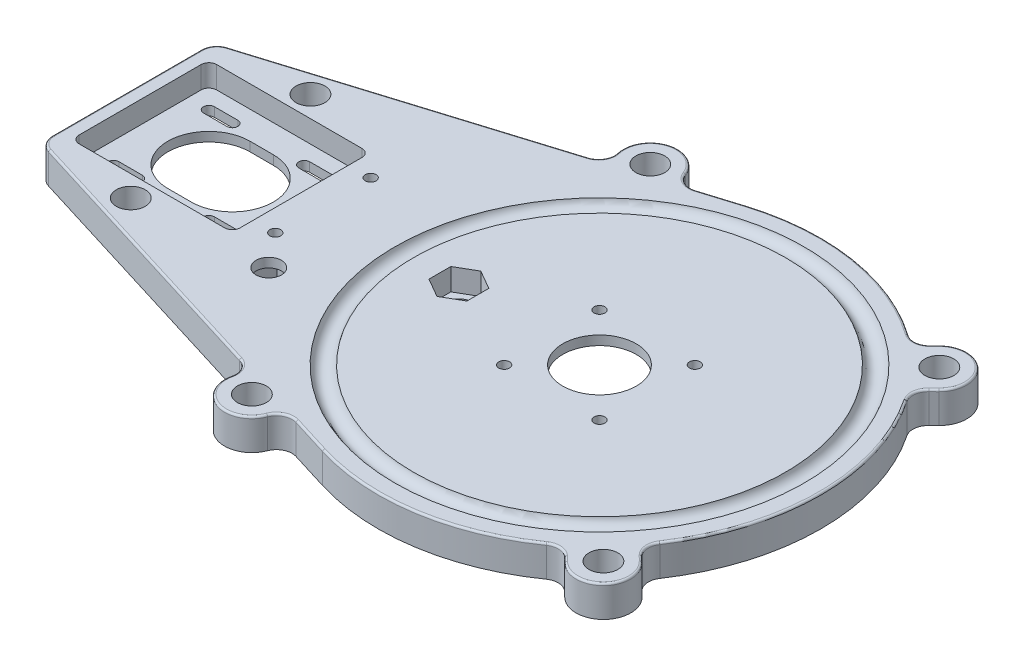
SolidWorks part; units mm, degrees
ref_plane "Front Plane" through (0, 0, 0) normal (0, 0, 1) x (1, 0, 0)
ref_plane "Top Plane" through (0, 0, 0) normal (0, 1, 0) x (1, 0, 0)
ref_plane "Right Plane" through (0, 0, 0) normal (1, 0, 0) x (0, 0, -1)
sketch "Sketch1" plane through (0, 0, 0) normal (0, 1, 0) x (1, 0, 0)
  line L0 (-153.67, 27.94) -> (-153.67, 0)
  line L5 (72.009, 0) -> (0, 0) construction
  line L6 (-153.67, 0) -> (-153.67, -27.94)
  line L7 (-21.2326, 68.8075) -> (-38.553, 63.4628)
  line L8 (-21.2326, -68.8075) -> (-38.553, -63.4628)
  line L9 (0, 0) -> (-153.67, 0) construction
  line L10 (0, 0) -> (55.88, 54.61) construction
  line L11 (55.88, 54.61) -> (55.88, 0) construction
  line L12 (55.88, -54.61) -> (0, 0) construction
  line L13 (55.88, 0) -> (55.88, -54.61) construction
  line L16 (-48.26, 64.77) -> (-48.26, 0) construction
  line L17 (-48.26, 0) -> (-48.26, -64.77) construction
  line L18 (49.6665, 60.968) -> (44.8924, 56.3025)
  line L19 (62.0935, -48.252) -> (57.3195, -43.5864)
  line L20 (49.6665, -60.968) -> (44.8924, -56.3025)
  line L21 (62.0935, -48.252) -> (55.88, -54.61) construction
  line L22 (55.88, -54.61) -> (49.6665, -60.968) construction
  line L23 (62.0935, 48.252) -> (57.3195, 43.5864)
  line L24 (62.0935, 48.252) -> (55.88, 54.61) construction
  line L25 (55.88, 54.61) -> (49.6665, 60.968) construction
  line L26 (-56.7548, 62.1487) -> (-55.5425, 58.2202)
  line L27 (-39.7652, 67.3913) -> (-38.553, 63.4628)
  line L28 (-39.7652, -67.3913) -> (-38.553, -63.4628)
  line L29 (-56.7548, -62.1487) -> (-55.5425, -58.2202)
  line L30 (-55.5425, -58.2202) -> (-153.67, -27.94)
  line L31 (-55.5425, 58.2202) -> (-153.67, 27.94)
  arc A0 (-21.2326, -68.8075) -> (44.8924, -56.3025) centre (0, 0) ccw
  circle A1 centre (55.88, 54.61) radius 2.5781
  circle A2 centre (55.88, -54.61) radius 2.5781
  arc A3 (49.6665, -60.968) -> (62.0935, -48.252) centre (55.88, -54.61) ccw
  arc A4 (62.0935, 48.252) -> (49.6665, 60.968) centre (55.88, 54.61) ccw
  arc A5 (57.3195, -43.5864) -> (57.3195, 43.5864) centre (0, 0) ccw
  arc A6 (44.8924, 56.3025) -> (-21.2326, 68.8075) centre (0, 0) ccw
  circle A9 centre (-48.26, 64.77) radius 2.5781
  circle A10 centre (-48.26, -64.77) radius 2.5781
  arc A11 (-39.7652, 67.3913) -> (-56.7548, 62.1487) centre (-48.26, 64.77) ccw
  arc A13 (-56.7548, -62.1487) -> (-39.7652, -67.3913) centre (-48.26, -64.77) ccw
  dimension "D4" = 144.018
  dimension "D3" = 5.1562
  dimension "D6" = 17.78
  dimension "D1" = 55.88
  dimension "D2" = 153.67
  dimension "D5" = 109.22
  dimension "D7" = 55.88
  dimension "D10" = 129.54
  dimension "D11" = 48.26
extrude "Boss-Extrude1" add sketch "Sketch1" along normal blind 10.16
fillet "Fillet1" radius 5.08 10 edges at (44.8924, 5.08, -56.3025) (44.8924, 5.08, 56.3025) (57.3195, 5.08, 43.5864) (57.3195, 5.08, -43.5864) (-153.67, 5.08, -27.94) (-153.67, 5.08, 27.94) (-38.553, 5.08, 63.4628) (-55.5425, 5.08, 58.2202) (-55.5425, 5.08, -58.2202) (-38.553, 5.08, -63.4628)
sketch "Sketch2" plane through (0, 10.16, 0) normal (0, 1, 0) x (1, 0, 0)
  line L1 (-15.5, 15.5) -> (15.5, 15.5) construction
  line L2 (-15.5, 15.5) -> (-15.5, -15.5) construction
  line L3 (-15.5, -15.5) -> (15.5, -15.5) construction
  line L4 (15.5, 15.5) -> (15.5, -15.5) construction
  line L5 (-15.5, 15.5) -> (15.5, -15.5) construction
  line L6 (-15.5, -15.5) -> (15.5, 15.5) construction
  circle A0 centre (0, 0) radius 11.938
  circle A1 centre (15.5, 15.5) radius 1.7653
  circle A2 centre (-15.5, 15.5) radius 1.7653
  circle A3 centre (-15.5, -15.5) radius 1.7653
  circle A4 centre (15.5, -15.5) radius 1.7653
  dimension "D1" = 23.876
  dimension "D3" = 3.5306
  dimension "D2" = 31
extrude "Holes-RStepperMotor" cut sketch "Sketch2" against normal through all
ref_axis "AxisOfRotation" through (0, 6.6675, 0) along (0, -1, 0)
sketch "Sketch3" plane through (0, 0, 0) normal (0, 0, -1) x (1, 0, 0)
  line L1 (-11.938, -10.16) -> (11.938, -10.16) construction
  line L2 (-11.938, -10.16) -> (11.938, -10.16) construction
  line L3 (-63.5, -7.747) -> (-63.5, -10.16) construction
  line L4 (-11.938, -10.16) -> (-63.5, -10.16) construction
  circle A0 centre (-63.5, -10.8712) radius 3.1242
  dimension "D2" = 6.2484
  dimension "D1" = 63.5
  dimension "D3" = 2.413
revolve "SlotForBalls" cut sketch "Sketch3" angle 360 about axis through (0, 6.6675, 0) along (0, -1, 0)
sketch "Sketch9" plane through (0, 10.16, 0) normal (0, 1, 0) x (1, 0, 0)
  line L0 (0, 0) -> (-45.72, 0) construction
  line L1 (0, 0) -> (-81.167, -26.3727) construction
  circle A2 centre (-45.72, 0) radius 4.1275
  circle A3 centre (-81.167, -26.3727) radius 4.1275
  dimension "D3" = 8.255
  dimension "D4" = 85.344
  dimension "D1" = 45.72
  dimension "D2" = 18
extrude "Holes-ProximitySensors" cut sketch "Sketch9" against normal through all
ref_plane "Plane-RStepperMotor" through (0, 7.16, 0) normal (0, 1, 0) x (1, 0, 0)
sketch "Sketch4" plane through (0, 0, 0) normal (0, -1, 0) x (1, 0, 0)
  line L1 (-22.86, 22.86) -> (22.86, 22.86)
  line L2 (-22.86, 22.86) -> (-22.86, -22.86)
  line L3 (-22.86, -22.86) -> (22.86, -22.86)
  line L4 (22.86, 22.86) -> (22.86, -22.86)
  line L5 (-22.86, 22.86) -> (22.86, -22.86) construction
  line L6 (-22.86, -22.86) -> (22.86, 22.86) construction
  line L7 (-84.7305, 20.2005) -> (-77.6034, 20.2005)
  line L8 (-77.6034, 20.2005) -> (-74.0399, 26.3727)
  line L9 (-74.0399, 26.3727) -> (-77.6034, 32.5449)
  line L10 (-77.6034, 32.5449) -> (-84.7305, 32.5449)
  line L11 (-84.7305, 32.5449) -> (-88.294, 26.3727)
  line L12 (-88.294, 26.3727) -> (-84.7305, 20.2005)
  circle A1 centre (-81.167, 26.3727) radius 6.1722 construction
  point P0 (0, 0)
  dimension "D2" = 12.3444
  dimension "D1" = 45.72
extrude "Relief-RStepperMotor" cut sketch "Sketch4" against normal up to surface (7.16 mm away)
ref_plane "Plane-ThetaStepperMotor" through (0, 3, 0) normal (0, -1, 0) x (-1, 0, 0)
sketch "Sketch7" plane through (0, 10.16, 0) normal (0, 1, 0) x (1, 0, 0)
  line L0 (0, 0) -> (-111.5, 0) construction
  line L1 (-142.5, 15.5) -> (-134.88, 15.5) construction
  line L2 (-142.5, 15.5) -> (-142.5, -15.5) construction
  line L3 (-142.5, -15.5) -> (-134.88, -15.5) construction
  line L4 (-111.5, 15.5) -> (-111.5, -15.5) construction
  line L5 (-134.88, -15.5) -> (-111.5, -15.5) construction
  line L6 (-111.5, -15.5) -> (-103.88, -15.5) construction
  line L7 (-134.88, 15.5) -> (-111.5, 15.5) construction
  line L8 (-111.5, 15.5) -> (-103.88, 15.5) construction
  line L9 (-111.5, 0) -> (-127, 0) construction
  line L10 (-127, 0) -> (-142.5, 0) construction
  line L11 (-127, 0) -> (-127, 15.5) construction
  line L12 (-127, 0) -> (-127, -15.5) construction
  line L13 (-142.5, 17.2653) -> (-134.88, 17.2653)
  line L14 (-103.88, 17.2653) -> (-111.5, 17.2653)
  line L15 (-142.5, 13.7347) -> (-134.88, 13.7347)
  line L16 (-103.88, 13.7347) -> (-111.5, 13.7347)
  line L17 (-111.5, 15.5) -> (-111.5, 17.2653) construction
  line L18 (-142.5, -17.2653) -> (-134.88, -17.2653)
  line L19 (-134.88, -13.7347) -> (-142.5, -13.7347)
  line L20 (-111.5, -17.2653) -> (-103.88, -17.2653)
  line L21 (-103.88, -13.7347) -> (-111.5, -13.7347)
  line L22 (-127, 13.335) -> (-119.38, 13.335)
  line L23 (-127, -13.335) -> (-119.38, -13.335)
  line L24 (-123.19, -13.335) -> (-123.19, -29.21) construction
  line L25 (-123.19, 13.335) -> (-123.19, 29.21) construction
  arc A0 (-127, 13.335) -> (-127, -13.335) centre (-127, 0) ccw
  arc A1 (-111.5, 17.2653) -> (-111.5, 13.7347) centre (-111.5, 15.5) ccw
  arc A2 (-142.5, 17.2653) -> (-142.5, 13.7347) centre (-142.5, 15.5) ccw
  arc A3 (-142.5, -13.7347) -> (-142.5, -17.2653) centre (-142.5, -15.5) ccw
  arc A4 (-111.5, -13.7347) -> (-111.5, -17.2653) centre (-111.5, -15.5) ccw
  arc A5 (-134.88, 13.7347) -> (-134.88, 17.2653) centre (-134.88, 15.5) ccw
  arc A6 (-103.88, 13.7347) -> (-103.88, 17.2653) centre (-103.88, 15.5) ccw
  arc A7 (-103.88, -17.2653) -> (-103.88, -13.7347) centre (-103.88, -15.5) ccw
  arc A8 (-134.88, -17.2653) -> (-134.88, -13.7347) centre (-134.88, -15.5) ccw
  arc A9 (-119.38, -13.335) -> (-119.38, 13.335) centre (-119.38, 0) ccw
  circle A10 centre (-123.19, -29.21) radius 2.5781
  circle A11 centre (-123.19, 29.21) radius 2.5781
  circle A13 centre (55.88, 54.61) radius 2.5781 construction
  dimension "D1" = 26.67
  dimension "D3" = 3.5306
  dimension "D2" = 31
  dimension "D4" = 58.42
  dimension "D5" = 7.62
  dimension "D6" = 123.19
extrude "Holes-ThetaStepperMotor" cut sketch "Sketch7" against normal through all
sketch "Sketch8" plane through (0, 10.16, 0) normal (0, 1, 0) x (1, 0, 0)
  line L4 (-123.19, -22.352) -> (-123.19, -15.5) construction
  line L5 (-142.5, 15.5) -> (-103.88, 15.5) construction
  line L6 (-142.5, 15.5) -> (-142.5, -15.5) construction
  line L7 (-142.5, -15.5) -> (-103.88, -15.5) construction
  line L8 (-103.88, 15.5) -> (-103.88, -15.5) construction
  line L9 (-149.352, 22.352) -> (-97.028, 22.352)
  line L10 (-149.352, 22.352) -> (-149.352, -22.352)
  line L11 (-149.352, -22.352) -> (-97.028, -22.352)
  line L12 (-97.028, 22.352) -> (-97.028, -22.352)
  line L14 (-103.88, 0) -> (-97.028, 0) construction
  line L15 (-45.72, -7.127) -> (-39.5478, -3.5635)
  line L16 (-123.19, 15.5) -> (-123.19, 22.352) construction
  line L17 (-39.5478, -3.5635) -> (-39.5478, 3.5635)
  line L18 (-142.5, 0) -> (-149.352, 0) construction
  line L19 (-39.5478, 3.5635) -> (-45.72, 7.127)
  line L20 (-45.72, 7.127) -> (-51.8922, 3.5635)
  line L21 (-51.8922, 3.5635) -> (-51.8922, -3.5635)
  line L22 (-51.8922, -3.5635) -> (-45.72, -7.127)
  circle A0 centre (-123.19, 29.21) radius 4.699
  circle A1 centre (-123.19, -29.21) radius 4.699
  circle A2 centre (-48.26, -64.77) radius 4.699
  circle A3 centre (55.88, -54.61) radius 4.699
  circle A4 centre (55.88, 54.61) radius 4.699
  circle A5 centre (-48.26, 64.77) radius 4.699
  circle A9 centre (-45.72, 0) radius 6.1722 construction
  circle A10 centre (-81.167, -26.3727) radius 6.1722 construction
  dimension "D2" = 9.398
  dimension "D1" = 44.704
extrude "Relief-ThetaStepperMotor" cut sketch "Sketch8" against normal up to surface (7.16 mm away)
fillet "Fillet-StepperMotors" radius 2.54 8 edges at (-22.86, 3.58, -22.86) (22.86, 3.58, -22.86) (22.86, 3.58, 22.86) (-22.86, 3.58, 22.86) (-149.352, 6.58, 22.352) (-97.028, 6.58, 22.352) (-97.028, 6.58, -22.352) (-149.352, 6.58, -22.352)
fillet "Fillet2" radius 0.635 26 edges at (-152.6775, 10.16, 27.2076) (-153.67, 10.16, 0) (-152.6775, 10.16, -27.2076) (-105.2262, 10.16, -42.8888) (-57.4559, 10.16, -59.0587) (-50.8813, 10.16, -73.2648) (-37.4448, 10.16, -65.2337) (-27.4818, 10.16, -66.8791) (11.3073, 10.16, -71.1157) (44.8602, 10.16, -57.9152) (48.8366, 10.16, -60.157) (62.238, 10.16, -60.8235) (61.2636, 10.16, -47.441) (58.931, 10.16, -43.5171) (72.009, 10.16, 0) (58.931, 10.16, 43.5171) (61.2636, 10.16, 47.441) (62.238, 10.16, 60.8235) (48.8366, 10.16, 60.157) (44.8602, 10.16, 57.9152) (11.3073, 10.16, 71.1157) (-27.4818, 10.16, 66.8791) (-37.4448, 10.16, 65.2337) (-50.8813, 10.16, 73.2648) (-57.4559, 10.16, 59.0587) (-105.2262, 10.16, 42.8888)
sketch "Sketch10" plane through (0, 10.16, 0) normal (0, 1, 0) x (1, 0, 0)
  line L0 (-103.88, 15.5) -> (-89.916, 15.5) construction
  line L1 (-89.916, 15.5) -> (-89.916, -15.5) construction
  line L2 (-89.916, -15.5) -> (-103.88, -15.5) construction
  line L3 (-97.028, -19.812) -> (-97.028, 19.812) construction
  circle A0 centre (-89.916, 15.5) radius 1.7653
  circle A1 centre (-89.916, -15.5) radius 1.7653
  circle A2 centre (-15.5, -15.5) radius 1.7653 construction
  dimension "D1" = 7.112
extrude "Holes-MotorSlideStop" cut sketch "Sketch10" against normal through all
